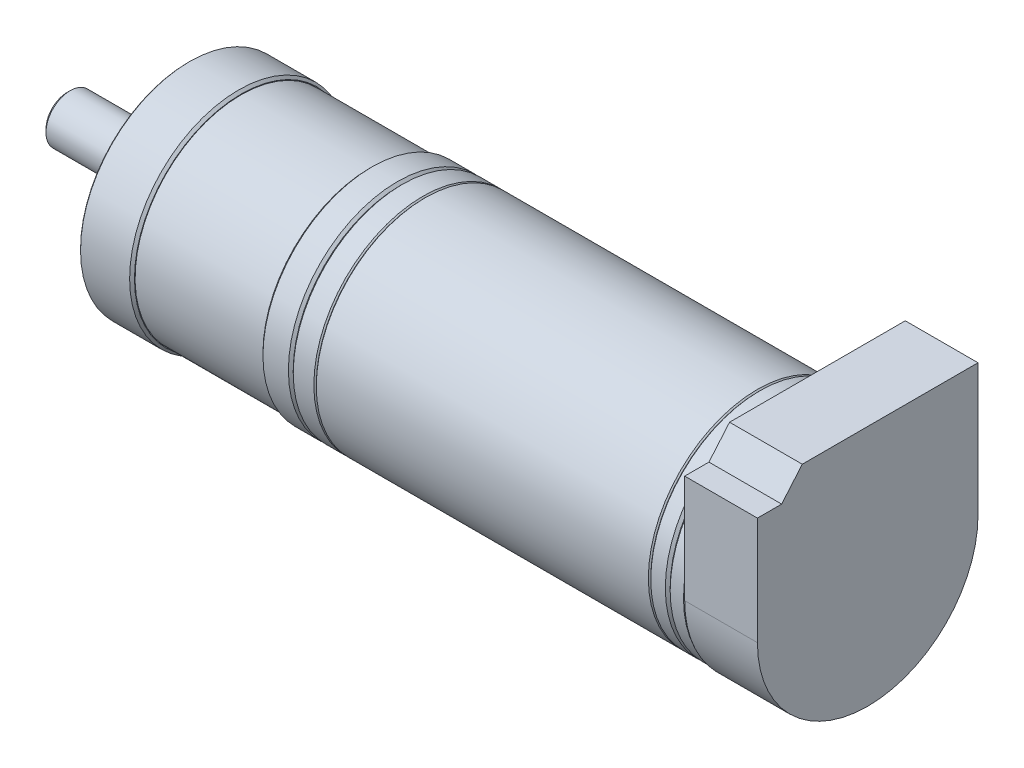
SolidWorks part; units mm, degrees
ref_plane "Front Plane" through (0, 0, 0) normal (0, 0, 1) x (1, 0, 0)
ref_plane "Top Plane" through (0, 0, 0) normal (0, 1, 0) x (1, 0, 0)
ref_plane "Right Plane" through (0, 0, 0) normal (1, 0, 0) x (0, 0, -1)
sketch "Sketch1" plane through (0, 0, 0) normal (0, 0, 1) x (1, 0, 0)
  line L0 (0, 0) -> (-120.1, 0) construction
  line L1 (-120.1, 0) -> (-120.1, 3.5)
  line L2 (-119.6, 4) -> (-102.1, 4)
  line L3 (-102.1, 4) -> (-102.1, 9.3)
  line L4 (-101.9, 11) -> (-100.1, 11)
  line L5 (-100.1, 11) -> (-100.1, 17.8)
  line L6 (-99.9, 18) -> (-91.8, 18)
  line L7 (-91.4, 17.6) -> (-91.4, 17.5)
  line L8 (-91.4, 17.5) -> (-70.2, 17.5)
  line L9 (-70.2, 17.5) -> (-70.2, 17.6)
  line L10 (-69.8, 18) -> (-65.6, 18)
  line L11 (-64.8, 18) -> (-61.4, 18)
  line L12 (-61, 18) -> (-6.2, 18)
  line L13 (-5.8, 18) -> (-3.4, 18)
  line L14 (-2.6, 18) -> (-0.4, 18)
  line L15 (0, 17.6) -> (0, 0)
  line L16 (-65.2, 18) -> (-65.2, 17.6) construction
  line L17 (-65.2, 17.6) -> (-65.6, 18)
  line L18 (-65.2, 17.6) -> (-64.8, 18)
  line L19 (-61.4, 18) -> (-61.2, 17.8)
  line L20 (-61.2, 17.8) -> (-61, 18)
  line L21 (-6.2, 18) -> (-6, 17.8)
  line L22 (-6, 17.8) -> (-5.8, 18)
  line L23 (-3.4, 18) -> (-3, 17.6)
  line L24 (-3, 17.6) -> (-2.6, 18)
  line L25 (-120.1, 3.5) -> (-119.6, 4)
  line L26 (-100.1, 17.8) -> (-99.9, 18)
  line L27 (-102.1, 10.8) -> (-101.9, 11)
  line L28 (-91.8, 18) -> (-91.4, 17.6)
  line L29 (-70.2, 17.6) -> (-69.8, 18)
  line L30 (-0.4, 18) -> (0, 17.6)
  line L31 (-65.2, 17.6) -> (0, 17.6) construction
  line L32 (-3, 18) -> (-3, 17.6) construction
  line L33 (-6, 18) -> (-6, 17.8) construction
  line L34 (-61.2, 18) -> (-61.2, 17.8) construction
  line L35 (0, 0) -> (-120.1, 0)
  line L36 (-102.1, 9.7) -> (-101.9, 9.5)
  line L37 (-101.9, 9.5) -> (-102.1, 9.3)
  line L38 (-102.1, 9.7) -> (-102.1, 10.8)
  point P5 (-120.1, 4)
  point P7 (-102.1, 11)
  point P10 (-91.4, 18)
  point P11 (-70.2, 18)
  point P16 (0, 18)
  point P29 (-100.1, 18)
  point P43 (-102, 9.4)
  dimension "D1" = 4
  dimension "D2" = 18
  dimension "D3" = 2
  dimension "D4" = 11
  dimension "D5" = 18
  dimension "D6" = 8.7
  dimension "D7" = 17.5
  dimension "D8" = 21.2
  dimension "D9" = 5
  dimension "D10" = 4
  dimension "D11" = 55.2
  dimension "D12" = 3
  dimension "D13" = 3
  dimension "D16" = 0.2
  dimension "D24" = 18
revolve "Revolve1" add sketch "Sketch1" angle 360 about L35
sketch "Sketch2" plane through (-100.1, 0, 0) normal (-1, 0, 0) x (0, 0, 1)
  line L0 (0, 0) -> (-15, 0) construction
  circle A0 centre (-15, 0) radius 1.5
  circle A2 centre (0, 15) radius 1.5
  circle A3 centre (15, 0) radius 1.5
  circle A4 centre (0, -15) radius 1.5
  point P13 (0, 0)
  dimension "D2" = 4
  dimension "D4" = 3
  dimension "D1" = 15
extrude "Cut-Extrude1" cut sketch "Sketch2" against normal blind 8
chamfer "Chamfer1" distance 0.5 angle 45 4 edges at (-100.1, -1.5, 15) (-100.1, -16.5, 0) (-100.1, -1.5, -15) (-100.1, 13.5, 0)
sketch "Sketch3" plane through (0, 0, 0) normal (1, 0, 0) x (0, 0, -1)
  line L0 (18.2, 21.8) -> (-10.8, 21.8)
  line L1 (-10.8, 21.8) -> (-14.2, 17.8)
  line L2 (-14.2, 17.8) -> (-18.2, 17.8)
  line L3 (-18.2, 17.8) -> (-18.2, 0)
  line L4 (18.2, 21.8) -> (18.2, 0)
  line L5 (0, 0) -> (-18.2, 0) construction
  line L6 (0, -18.2) -> (0, -20.2) construction
  line L7 (-2.5, -18.0275) -> (2.5, -18.0275) construction
  line L8 (-2.5, -18.0275) -> (-2.5, -19.0275)
  line L9 (2.5, -19.0275) -> (2.5, -18.0275)
  arc A0 (-18.2, 0) -> (-2.5, -18.0275) centre (0, 0) ccw
  arc A2 (-2.5, -19.0275) -> (2.5, -19.0275) centre (0, -16.9485) ccw
  arc A3 (2.5, -18.0275) -> (18.2, 0) centre (0, 0) ccw
  dimension "D1" = 36.4
  dimension "D2" = 21.8
  dimension "D3" = 29
  dimension "D4" = 4
  dimension "D5" = 4
  dimension "D6" = 5
  dimension "D7" = 2
  dimension "D8" = 1
extrude "Boss-Extrude1" add sketch "Sketch3" along normal blind 12
sketch "Sketch4" plane through (12, 0, 0) normal (1, 0, 0) x (0, 0, -1)
  line L0 (2.5, -19.0275) -> (2.5, -18.0275) construction
  line L1 (-2.5, -18.0275) -> (-2.5, -19.0275) construction
  line L2 (2.5, -19.0275) -> (2.5, -18.0275)
  line L3 (-2.5, -18.0275) -> (-2.5, -19.0275)
  arc A0 (-2.5, -18.0275) -> (2.5, -18.0275) centre (0, 0) ccw
  arc A1 (-18.2, 0) -> (-2.5, -18.0275) centre (0, 0) ccw construction
  arc A2 (-2.5, -19.0275) -> (2.5, -19.0275) centre (0, -16.9485) ccw construction
  arc A3 (-2.5, -19.0275) -> (2.5, -19.0275) centre (0, -16.9485) ccw
extrude "Cut-Extrude2" cut sketch "Sketch4" against normal blind 5
